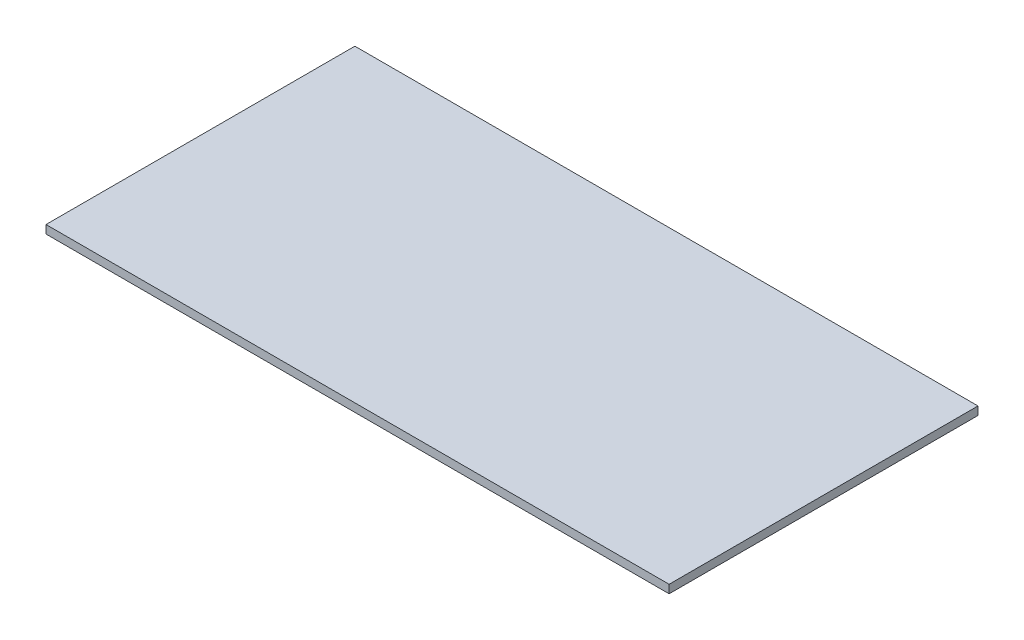
SolidWorks part; units mm, degrees
ref_plane "Front Plane" through (0, 0, 0) normal (0, 0, 1) x (1, 0, 0)
ref_plane "Top Plane" through (0, 0, 0) normal (0, 1, 0) x (1, 0, 0)
ref_plane "Right Plane" through (0, 0, 0) normal (1, 0, 0) x (0, 0, -1)
sketch "Sketch1" plane through (0, 0, 0) normal (0, 1, 0) x (1, 0, 0)
  line L5 (-75.35, 37.35) -> (75.35, 37.35)
  line L6 (-75.35, 37.35) -> (-75.35, -37.35)
  line L7 (-75.35, -37.35) -> (75.35, -37.35)
  line L8 (75.35, 37.35) -> (75.35, -37.35)
  line L9 (-75.35, 37.35) -> (75.35, -37.35) construction
  line L10 (-75.35, -37.35) -> (75.35, 37.35) construction
  point P0 (0, 0)
  dimension "D1" = 150.7
  dimension "D2" = 74.7
extrude "Boss-Extrude1" add sketch "Sketch1" along normal blind 2
